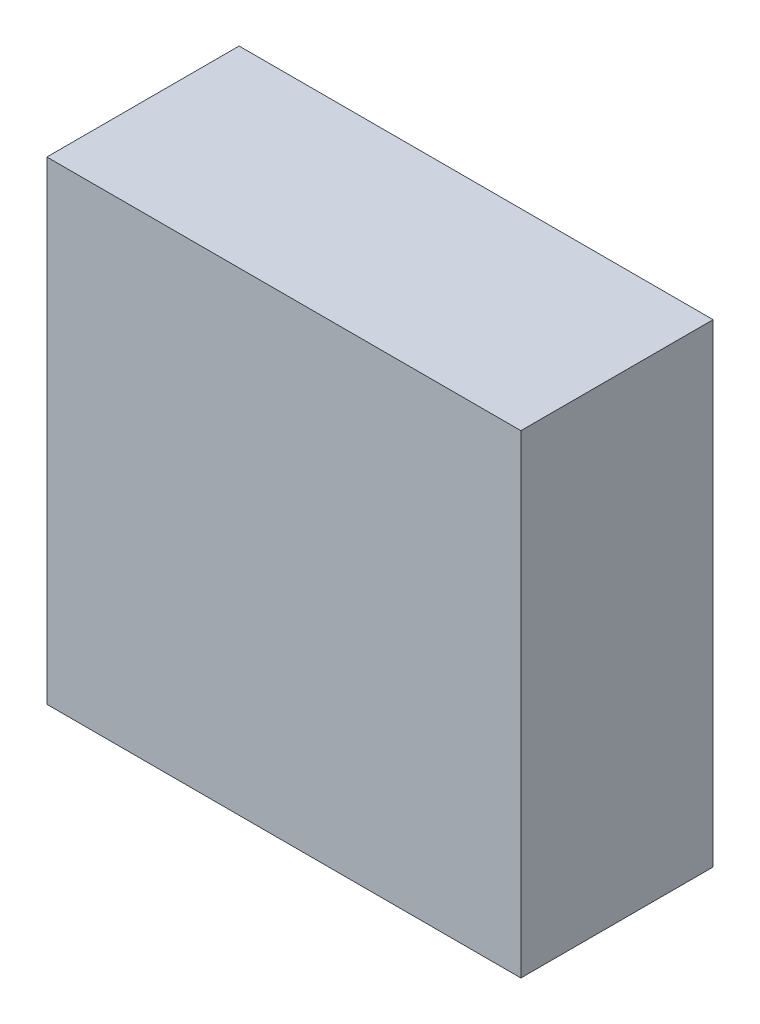
SolidWorks part; units mm, degrees
ref_plane "Front Plane" through (0, 0, 0) normal (0, 0, 1) x (1, 0, 0)
ref_plane "Top Plane" through (0, 0, 0) normal (0, 1, 0) x (1, 0, 0)
ref_plane "Right Plane" through (0, 0, 0) normal (1, 0, 0) x (0, 0, -1)
sketch "Sketch1" plane through (0, 0, 0) normal (0, 0, 1) x (1, 0, 0)
  line L1 (0, 0) -> (45, 0)
  line L2 (0, 0) -> (0, -45)
  line L3 (0, -45) -> (45, -45)
  line L4 (45, 0) -> (45, -45)
  dimension "D1" = 45
  dimension "D2" = 45
extrude "Boss-Extrude1" add sketch "Sketch1" along normal blind 18.25
